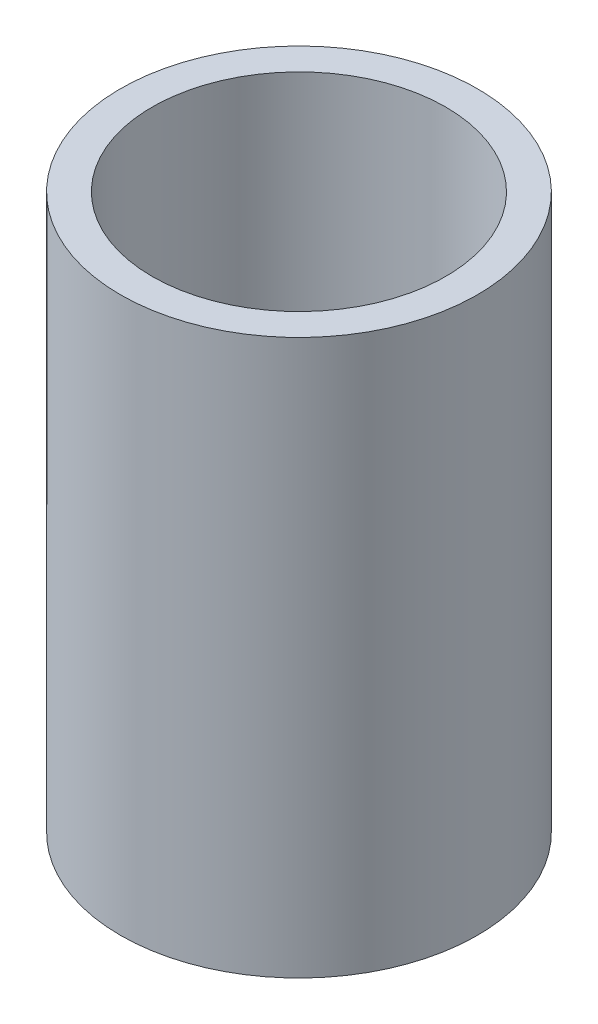
SolidWorks part; units mm, degrees
material "Thornel Mat VMA"
ref_plane "Front Plane" through (0, 0, 0) normal (0, 0, 1) x (1, 0, 0)
ref_plane "Top Plane" through (0, 0, 0) normal (0, 1, 0) x (1, 0, 0)
ref_plane "Right Plane" through (0, 0, 0) normal (1, 0, 0) x (0, 0, -1)
sketch "Sketch1" plane through (0, 0, 0) normal (0, 1, 0) x (1, 0, 0)
  circle A0 centre (0, 0) radius 7.9375
  circle A1 centre (0, 0) radius 9.652
  dimension "D1" = 15.875
  dimension "D2" = 19.304
extrude "Boss-Extrude1" add sketch "Sketch1" along normal blind 30
